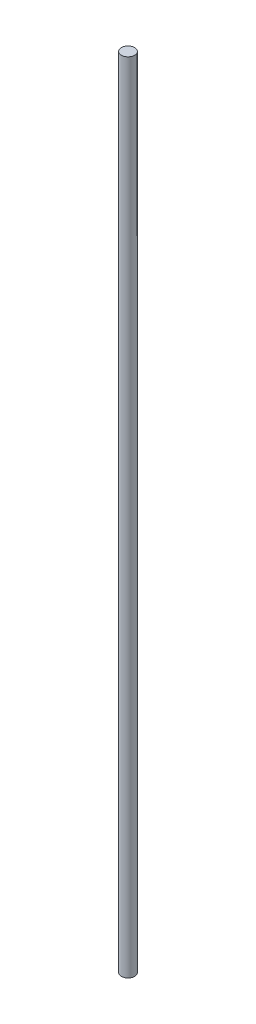
SolidWorks part; units mm, degrees
material "1060-H12"
ref_plane "Front Plane" through (0, 0, 0) normal (0, 0, 1) x (1, 0, 0)
ref_plane "Top Plane" through (0, 0, 0) normal (0, 1, 0) x (1, 0, 0)
ref_plane "Right Plane" through (0, 0, 0) normal (1, 0, 0) x (0, 0, -1)
sketch "Sketch1" plane through (0, 0, 0) normal (0, 1, 0) x (1, 0, 0)
  circle A0 centre (0, 0) radius 3
  dimension "D1" = 6
extrude "Boss-Extrude1" add sketch "Sketch1" along normal blind 360 contours A0
